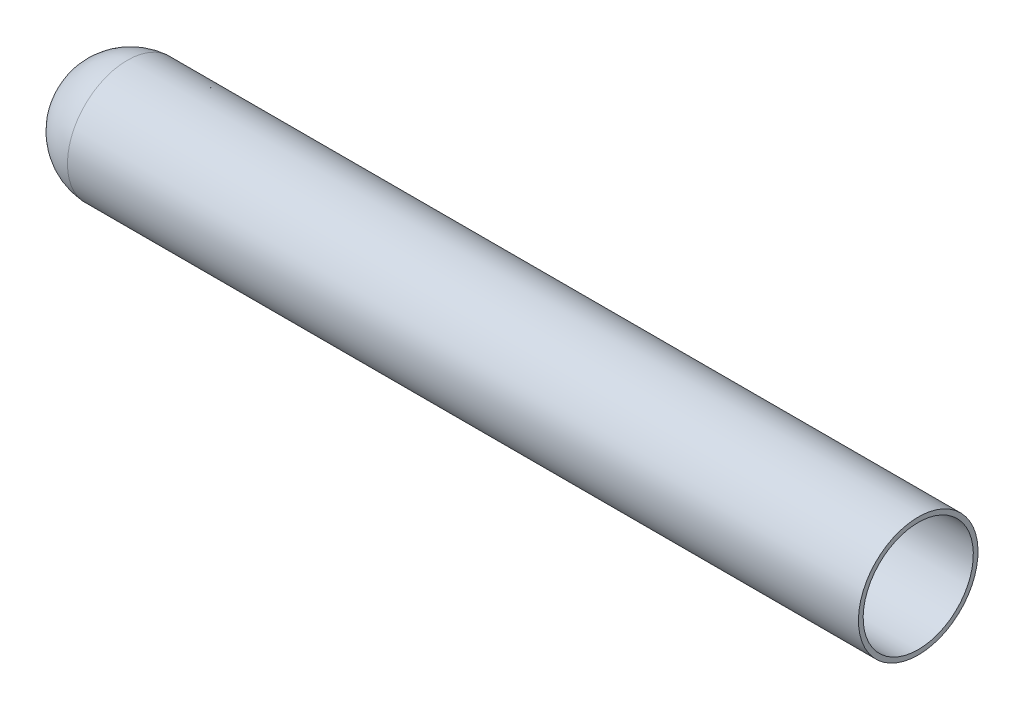
SolidWorks part; units mm, degrees
material "Polieter Polyol"
ref_plane "Ön Düzlem" through (0, 0, 0) normal (0, 0, 1) x (1, 0, 0)
ref_plane "Üst Düzlem" through (0, 0, 0) normal (0, 1, 0) x (1, 0, 0)
ref_plane "Sağ Düzlem" through (0, 0, 0) normal (1, 0, 0) x (0, 0, -1)
sketch "Çizim1" plane through (0, 0, 0) normal (0, 0, 1) x (1, 0, 0)
  line L2 (45, 3.175) -> (3, 3.175)
  line L3 (45, 2.925) -> (3.0072, 2.925)
  line L4 (45, 2.925) -> (45, 3.175)
  line L5 (0.25, 0) -> (0, 0)
  line L6 (0.25, 0) -> (45, 0) construction
  arc A0 (3, 3.175) -> (0, 0) centre (3.1801, 0) ccw
  arc A1 (3.0072, 2.925) -> (0.25, 0) centre (3.1801, 0) ccw
  point P6 (0, 0)
  dimension "D1" = 3.175
  dimension "D2" = 45
  dimension "D3" = 42
  dimension "D4" = 0.25
revolve "Döndür1" add sketch "Çizim1" angle 360 about L6
